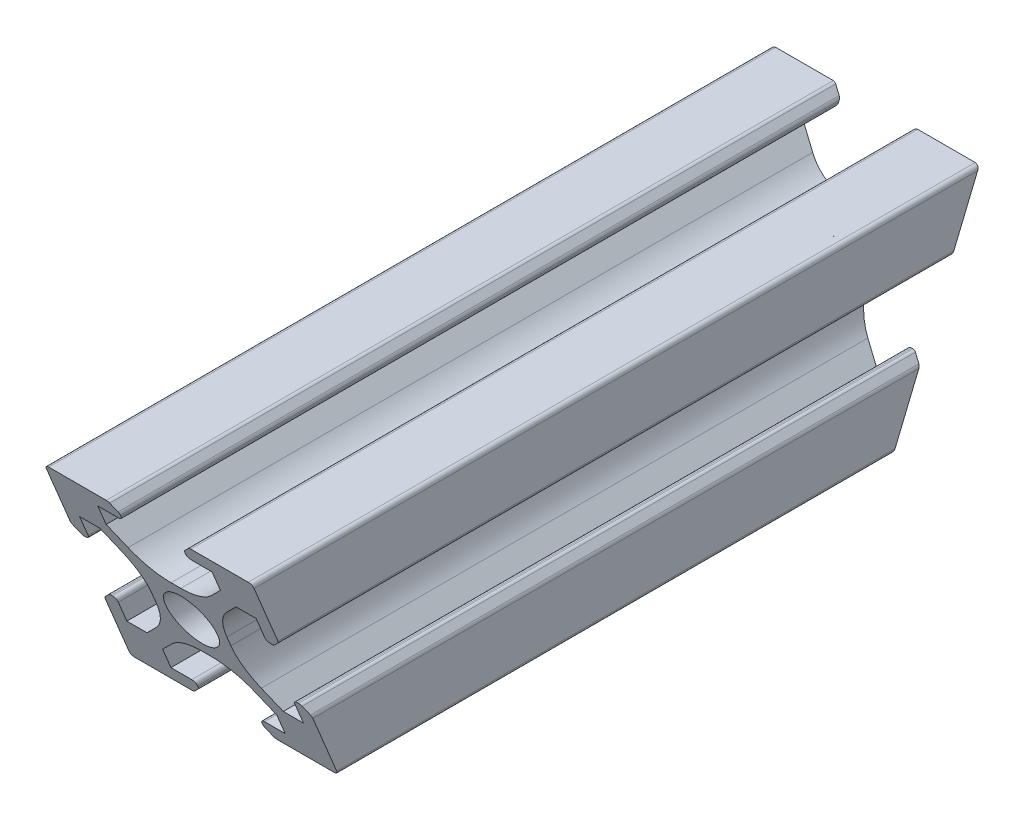
SolidWorks part; units mm, degrees
material "6063-O"
ref_plane "Plano frontal" through (0, 0, 0) normal (0, 0, 1) x (1, 0, 0)
ref_plane "Plano superior" through (0, 0, 0) normal (0, 1, 0) x (1, 0, 0)
ref_plane "Plano direito" through (0, 0, 0) normal (1, 0, 0) x (0, 0, -1)
sketch "Esboço1" plane through (0, 0, 0) normal (0, 0, 1) x (1, 0, 0)
  line L0 (-9.0343, 3.1) -> (-8.9, 3.1)
  line L3 (-10, 10) -> (-4.0657, 10)
  line L5 (-10, -10) -> (10, 10) construction
  line L6 (-10, 10) -> (10, -10) construction
  line L7 (-8.5, 3.5) -> (-8.5, 5.5)
  line L8 (-10, 0) -> (10, 0) construction
  line L9 (0, 10) -> (0, -10) construction
  line L12 (-8.5, 5.5) -> (-6.5607, 5.5)
  line L15 (-6.5607, 5.5) -> (-5.0645, 4.0038)
  line L16 (-3.6, 0.4683) -> (-3.6, 0)
  line L17 (-0.4683, 3.6) -> (0, 3.6)
  line L18 (-5.5, 6.5607) -> (-4.0038, 5.0645)
  line L21 (-5.5, 8.5) -> (-5.5, 6.5607)
  line L24 (-3.5, 8.5) -> (-5.5, 8.5)
  line L25 (-3.1, 9.0343) -> (-3.1, 8.9)
  line L44 (-10, 4.0657) -> (-10, 10)
  line L45 (-9.8828, 3.7828) -> (-9.3172, 3.2172)
  line L46 (-3.7828, 9.8828) -> (-3.2172, 9.3172)
  line L47 (-3.6, 0) -> (-2.5, 0)
  line L48 (0, 3.6) -> (0, 2.5)
  arc A0 (-3.5, 8.5) -> (-3.1, 8.9) centre (-3.5, 8.9) ccw
  arc A1 (-3.7828, 9.8828) -> (-4.0657, 10) centre (-4.0657, 9.6) ccw
  arc A2 (-10, 4.0657) -> (-9.8828, 3.7828) centre (-9.6, 4.0657) ccw
  arc A3 (-8.5, 3.5) -> (-8.9, 3.1) centre (-8.9, 3.5) cw
  arc A4 (-3.2172, 9.3172) -> (-3.1, 9.0343) centre (-3.5, 9.0343) cw
  arc A5 (-9.3172, 3.2172) -> (-9.0343, 3.1) centre (-9.0343, 3.5) ccw
  arc A6 (-3.6, 0.4683) -> (-5.0645, 4.0038) centre (-8.6, 0.4683) ccw
  arc A7 (-4.0038, 5.0645) -> (-0.4683, 3.6) centre (-0.4683, 8.6) ccw
  circle A8 centre (0, 0) radius 2.5
  point P6 (-10, 3.1)
  point P28 (-3.1, 8.5)
  point P31 (-3.1, 10)
  point P33 (-3.9, 10)
  point P36 (-10, 3.9)
  point P39 (-8.5, 3.1)
  point P42 (-3.1, 9.2)
  point P45 (-9.2, 3.1)
  point P48 (-3.6, 2.5393)
  point P51 (-2.5393, 3.6)
  dimension "D5" = 10
  dimension "D9" = 0.4
  dimension "D10" = 0.4
  dimension "D11" = 5
  dimension "D12" = 5
  dimension "D13" = 5
  dimension "D1" = 6.9
  dimension "D2" = 1.5
  dimension "D3" = 3.6
  dimension "D4" = 1.5
  dimension "D6" = 2.4
  dimension "D7" = 3.6
  dimension "D8" = 45
extrude "Ressalto-extrusão1" add sketch "Esboço1" along normal blind 70
sketch "Esboço3" plane through (0, 0, 0) normal (1, 0, 0) x (0, 0, -1)
  line L0 (0, 0) -> (-70, 0) construction
  line L1 (-70, 2.5) -> (-70, 0) construction
pattern_circular "PadrãoCircular1" count 4 every 90 about axis through (0, 0, 0) along (0, 0, 1) of "Ressalto-extrusão1"
fillet "Filete1" radius 0.4 4 edges at (-10, -10, 35) (-10, 10, 35) (10, -10, 35) (10, 10, 35)
ref_plane "Plane1" through (0, 0, 35) normal (0, 0, 1) x (1, 0, 0)
sketch "Sketch1" plane through (-10, 0, 0) normal (-1, 0, 0) x (0, 0, 1)
  line L0 (0, 10) -> (0, -10)
  line L1 (0, 0) -> (70, 0) construction
  line L2 (0, 10) -> (8.2843, -10)
  line L3 (0, -10) -> (8.2843, -10)
  line L4 (35, 9.6) -> (35, -9.6) construction
  line L5 (70, 9.6) -> (0, 9.6) construction
  line L6 (0, -9.6) -> (70, -9.6) construction
  line L7 (70, 9.6) -> (70, -9.6)
  line L8 (70, -10) -> (61.7157, -10)
  line L9 (70, 10) -> (61.7157, -10)
  line L10 (70, 10) -> (70, -10)
  line M5 (70, 4.0657) -> (70, 9.6)
  line M6 (70, 9.6) -> (0, 9.6)
  line M7 (0, 9.6) -> (0, 4.0657)
  line M8 (0, 4.0657) -> (70, 4.0657)
  dimension "D1" = 10
  dimension "D2" = 22.5
extrude "Cut-Extrude1" cut sketch "Sketch1" against normal through all contours L0 L3 L2 M8 | L2 M6 M7 M8 | L9 M6 M8 M5 | L10 L7 L9 L8 M8 | L10 L9 M6 | L2 L0 M6
sketch "Sketch2" plane through (-10, 0, 0) normal (-1, 0, 0) x (0, 0, 1)
  line L0 (35, -9.6) -> (35, 9.6) construction
  line L1 (8.1186, -9.6) -> (61.8814, -9.6) construction
  line L2 (69.8343, 9.6) -> (0.1657, 9.6) construction
  line L3 (0, 0) -> (80.4315, 0) construction
  circle A1 centre (11, 0) radius 1.5
  circle A3 centre (59, 0) radius 1.5
  dimension "D3" = 3
  dimension "D2" = 11
extrude "Cut-Extrude2" cut sketch "Sketch2" against normal through all
